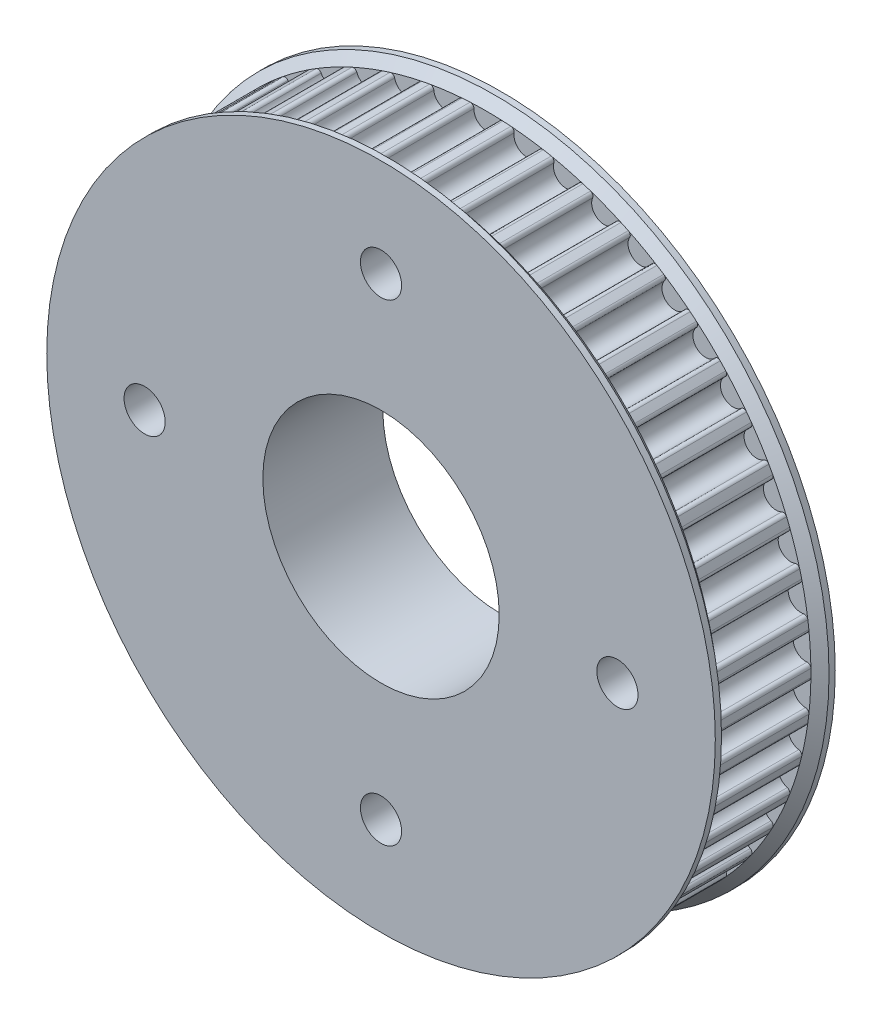
SolidWorks part; units mm, degrees
material "Nailon 6/10"
ref_plane "Alzado" through (0, 0, 0) normal (0, 0, 1) x (1, 0, 0)
ref_plane "Planta" through (0, 0, 0) normal (0, 1, 0) x (1, 0, 0)
ref_plane "Vista lateral" through (0, 0, 0) normal (1, 0, 0) x (0, 0, -1)
sketch "Croquis2" plane through (0, 0, 0) normal (0, 0, 1) x (1, 0, 0)
  circle A0 centre (0, 0) radius 39.2172
  dimension "D1" = 78.4345
extrude "Saliente-Extruir1" add sketch "Croquis2" along normal mid plane 11
sketch "Croquis4" plane through (0, 0, 0) normal (0, 0, 1) x (1, 0, 0)
  line L0 (0, 0) -> (0, 38.6822) construction
  line L1 (0, 0) -> (4.8482, 38.3772) construction
  circle A0 centre (0, 0) radius 37.1572
  circle A1 centre (0, 38.6822) radius 1.525 construction
  circle A2 centre (4.8482, 38.3772) radius 1.525 construction
  circle A3 centre (1.9542, 38.738) radius 0.43 construction
  circle A4 centre (0, 0) radius 39.2172 construction
  circle A5 centre (2.9164, 38.6774) radius 0.43 construction
  arc A6 (-1.5244, 38.7257) -> (1.5244, 38.7257) centre (0, 38.6822) ccw
  arc A7 (1.5244, 38.7257) -> (1.9759, 39.1674) centre (1.9542, 38.738) cw
  arc A8 (2.9487, 39.1062) -> (1.9759, 39.1674) centre (0, 0) ccw
  arc A9 (2.9487, 39.1062) -> (3.3413, 38.6114) centre (2.9164, 38.6774) cw
  arc A10 (3.3413, 38.6114) -> (4.657, 36.8642) centre (4.8482, 38.3772) ccw
  arc A11 (-3.3413, 38.6114) -> (-4.657, 36.8642) centre (-4.8482, 38.3772) cw
  arc A12 (-2.9487, 39.1062) -> (-3.3413, 38.6114) centre (-2.9164, 38.6774) ccw
  arc A13 (-2.9487, 39.1062) -> (-1.9759, 39.1674) centre (0, 0) cw
  arc A14 (-1.5244, 38.7257) -> (-1.9759, 39.1674) centre (-1.9542, 38.738) ccw
  arc A15 (-1.9759, 39.1674) -> (1.9759, 39.1674) centre (0, 0) cw
  dimension "D1" = 74.3145
  dimension "D3" = 3.05
  dimension "D4" = 0.86
  dimension "D2" = 7.2
extrude "Cortar-Extruir2" cut sketch "Croquis4" against normal through all both and the other way through all contours A15 A14 A6 A7
pattern_circular "MatrizC4" count 50 over 360 about axis through (0, 0, 0) along (0, 0, 1) of "Cortar-Extruir2"
sketch "Croquis5" plane through (0, 0, 0) normal (0, 1, 0) x (1, 0, 0)
  line L0 (0, 0) -> (0, 5.5) construction
  line L1 (1.525, 5.5) -> (-1.525, 5.5) construction
  line L2 (0, 5.5) -> (39.2172, 5.5)
  line L3 (39.2172, 5.5) -> (40.409, 6.5)
  line L4 (40.409, 6.5) -> (40.409, 7.25)
  line L5 (40.409, 7.25) -> (0, 7.25)
  line L6 (0, 7.25) -> (0, 5.5)
  line L7 (0, 0) -> (39.2172, 0) construction
  line L9 (0, -7.25) -> (0, -5.5)
  line L10 (40.409, -7.25) -> (0, -7.25)
  line L11 (40.409, -6.5) -> (40.409, -7.25)
  line L12 (39.2172, -5.5) -> (40.409, -6.5)
  line L13 (0, -5.5) -> (39.2172, -5.5)
  dimension "D1" = 50
  dimension "D2" = 1.75
  dimension "D3" = 0.75
  dimension "D4" = 78.4345
revolve "Revolución1" add sketch "Croquis5" angle 360 about L0
sketch "Croquis6" plane through (0, 0, 0) normal (0, 0, 1) x (1, 0, 0)
  line L1 (3.6882, -6.3881) -> (7.3763, 0)
  line L2 (7.3763, 0) -> (3.6882, 6.3881)
  line L3 (3.6882, 6.3881) -> (-2.9954, 6.3881)
  line L4 (-4.0346, 5.7881) -> (-7.3763, 0)
  line L5 (-7.3763, 0) -> (-3.6882, -6.3881)
  line L6 (-3.6882, -6.3881) -> (3.6882, -6.3881)
  line L7 (-3.6882, 6.3881) -> (-7.3763, 0)
  line L8 (-7.3763, 0) -> (-3.6882, -6.3881)
  line L9 (-3.6882, -6.3881) -> (3.6882, -6.3881)
  line L10 (3.6882, -6.3881) -> (7.3763, 0)
  line L11 (7.3763, 0) -> (3.6882, 6.3881)
  line L12 (3.6882, 6.3881) -> (-3.6882, 6.3881)
  circle A0 centre (0, 0) radius 6.3881 construction
  arc A1 (-3.3418, 6.5881) -> (-4.0346, 6.1881) centre (-3.6882, 6.3881) ccw
  arc A2 (-4.0346, 5.7881) -> (-4.0346, 6.1881) centre (-4.381, 5.9881) ccw
  arc A3 (-2.9954, 6.3881) -> (-3.3418, 6.5881) centre (-2.9954, 6.7881) cw
  circle A4 centre (0, 0) radius 6.3881 construction
  arc A5 (4.0346, 5.7881) -> (4.0346, 6.1881) centre (4.381, 5.9881) cw
  arc A6 (4.0346, 6.1881) -> (3.3418, 6.5881) centre (3.6882, 6.3881) ccw
  arc A7 (2.9954, 6.3881) -> (3.3418, 6.5881) centre (2.9954, 6.7881) ccw
  arc A8 (7.0299, -0.6) -> (7.3763, -0.4) centre (7.3763, -0.8) cw
  arc A9 (7.3763, -0.4) -> (7.3763, 0.4) centre (7.3763, 0) ccw
  arc A10 (7.0299, 0.6) -> (7.3763, 0.4) centre (7.3763, 0.8) ccw
  arc A11 (2.9954, -6.3881) -> (3.3418, -6.5881) centre (2.9954, -6.7881) cw
  arc A12 (3.3418, -6.5881) -> (4.0346, -6.1881) centre (3.6882, -6.3881) ccw
  arc A13 (4.0346, -5.7881) -> (4.0346, -6.1881) centre (4.381, -5.9881) ccw
  arc A14 (-4.0346, -5.7881) -> (-4.0346, -6.1881) centre (-4.381, -5.9881) cw
  arc A15 (-4.0346, -6.1881) -> (-3.3418, -6.5881) centre (-3.6882, -6.3881) ccw
  arc A16 (-2.9954, -6.3881) -> (-3.3418, -6.5881) centre (-2.9954, -6.7881) ccw
  arc A17 (-7.0299, 0.6) -> (-7.3763, 0.4) centre (-7.3763, 0.8) cw
  arc A18 (-7.3763, 0.4) -> (-7.3763, -0.4) centre (-7.3763, 0) ccw
  arc A19 (-7.0299, -0.6) -> (-7.3763, -0.4) centre (-7.3763, -0.8) ccw
  point P54 (0, 0)
  dimension "D1" = 12.7762
  dimension "D2" = 0.8
  dimension "D3" = 0.4
  dimension "D4" = 0.4
  dimension "D5" = 6
extrude "Cortar-Extruir3" cut sketch "Croquis6" against normal through all both and the other way through all contours L3 L12 L7 L4 L5 L8 L6 L9 L1 L10 L2 L11 | A7 L3 L11 A5 A6 | L12 A3 A1 A2 L7 | A19 L5 L7 A17 A18 | A16 L6 L8 A14 A15 | A13 L1 L9 A11 A12 | A10 L2 L10 A8 A9
sketch "Croquis7" plane through (0, 0, 7.25) normal (0, 0, 1) x (1, 0, 0)
  circle A0 centre (0, 0) radius 14.2875
  circle A1 centre (0, 0) radius 28.575 construction
  circle A2 centre (0, 28.575) radius 2.4892
  circle A3 centre (-28.575, 0) radius 2.4892
  circle A4 centre (0, -28.575) radius 2.4892
  circle A5 centre (28.575, 0) radius 2.4892
  dimension "D1" = 57.15
  dimension "D2" = 28.575
  dimension "D3" = 4.9784
extrude "Cortar-Extruir4" cut sketch "Croquis7" against normal through all
equation "\"X\"= \"DimCal\""
equation "\"Y\"= \"X\" - ( 2 * 2.06 )"
equation "\"Nt\"= 50'Numero de dientes ( Minimo 10 reco 18)"
equation "\"A\"= 360° / \"Nt\""
equation "\"G\"= 11mm"
equation "\"D1@Croquis2\"=\"X\""
equation "\"D1@Saliente-Extruir1\"=\"G\""
equation "\"D1@Croquis4\"=\"Y\""
equation "\"D2@Croquis4\"=\"A\""
equation "\"D1@MatrizC4\"=\"Nt\""
equation "\"TP\"= 5mm'Tooth pitch"
equation "\"PLO\"= 0.5715mm'Pitch line offset"
equation "\"DimCal\"= 2 * ( ( \"Nt\" * \"TP\" ) / ( pi * 2 ) - \"PLO\" )'Diameter (calculated)"
equation "\"D4@Croquis5\"=\"X\""
